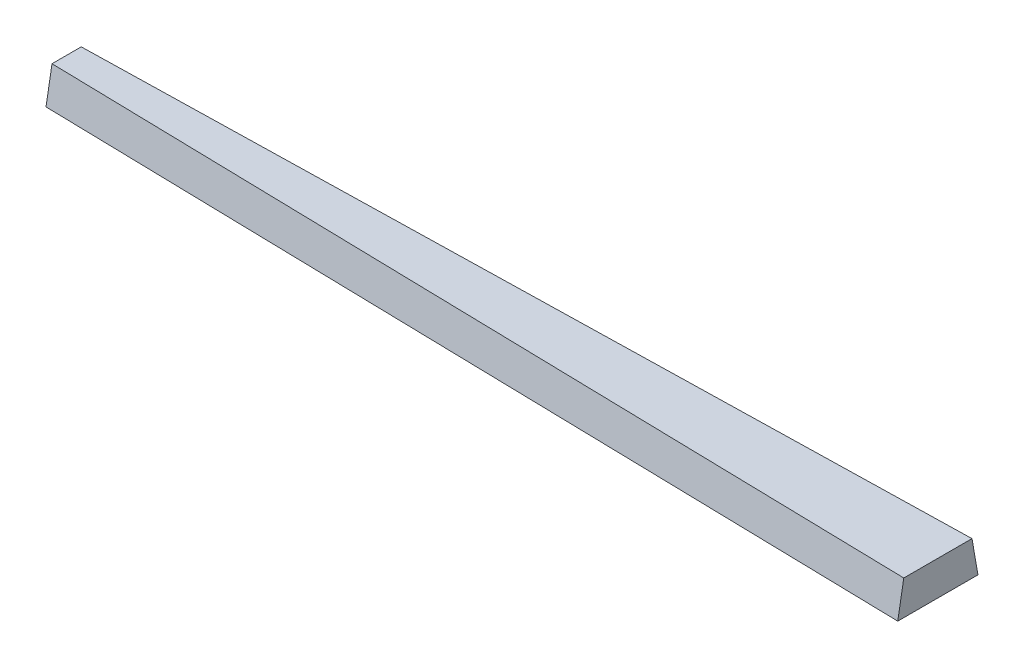
SolidWorks part; units mm, degrees
ref_plane "Front Plane" through (0, 0, 0) normal (0, 0, 1) x (1, 0, 0)
ref_plane "Top Plane" through (0, 0, 0) normal (0, 1, 0) x (1, 0, 0)
ref_plane "Right Plane" through (0, 0, 0) normal (1, 0, 0) x (0, 0, -1)
sketch "Sketch1" plane through (0, 0, 0) normal (0, 1, 0) x (1, 0, 0)
  line L1 (-241.3, -25.4) -> (241.3, -25.4)
  line L2 (-241.3, -25.4) -> (-241.3, 25.4)
  line L3 (-241.3, 25.4) -> (241.3, 25.4)
  line L4 (241.3, -25.4) -> (241.3, 25.4)
  line L5 (-241.3, -25.4) -> (241.3, 25.4) construction
  line L6 (-241.3, 25.4) -> (241.3, -25.4) construction
  point P0 (0, 0)
  dimension "D1" = 50.8
  dimension "D2" = 482.6
extrude "Boss-Extrude1" add sketch "Sketch1" along normal blind 19.05
sketch "Sketch2" plane through (241.3, 0, 0) normal (1, 0, 0) x (0, 0, -1)
  line L3 (25.4, 19.05) -> (25.4, 0) construction
  line L8 (-18.89, 19.05) -> (0, 19.05) construction
  line L11 (-25.4, 19.05) -> (25.4, 19.05) construction
  line L12 (0, 19.05) -> (0, 0) construction
  line L13 (0, 0) -> (-22.225, 0) construction
  line L14 (-25.4, 0) -> (25.4, 0) construction
  line L15 (-22.225, 0) -> (-18.89, 19.05) construction
  dimension "Top Angle" = 80.07
  dimension "Top width" = 22.225
sketch "Sketch3" plane through (-241.3, 0, 0) normal (-1, 0, 0) x (0, 0, 1)
  line L4 (8.095, 19.05) -> (0, 19.05) construction
  line L6 (0, 19.05) -> (0, 0) construction
  line L7 (0, 0) -> (11.43, 0) construction
  line L9 (11.43, 0) -> (8.095, 19.05) construction
  line L11 (-25.4, 19.05) -> (25.4, 19.05) construction
  line L12 (-25.4, 0) -> (25.4, 0) construction
  dimension "bottomwidth" = 11.43
  dimension "bottomangle" = 80.07
ref_plane "Plane1" through (-0.365, 2.857, 16.3192) normal (-0.022, 0.1724, 0.9848) x (0.9998, 0.0038, 0.0217)
sketch "Sketch5" plane through (-0.365, 2.857, 16.3192) normal (-0.022, 0.1724, 0.9848) x (0.9998, 0.0038, 0.0217)
  line L0 (0, 0) -> (0, 35.0975) construction
  line L1 (-254, 35.0975) -> (254, 35.0975)
  line L2 (-254, 35.0975) -> (-254, -15.7025)
  line L3 (-254, -15.7025) -> (254, -15.7025)
  line L4 (254, 35.0975) -> (254, -15.7025)
  dimension "D1" = 508
  dimension "D2" = 50.8
extrude "Cut-Extrude1" cut sketch "Sketch5" along normal through all
mirror "Mirror1" about plane through (0, 0, 0) normal (0, 0, 1) of "Cut-Extrude1"
